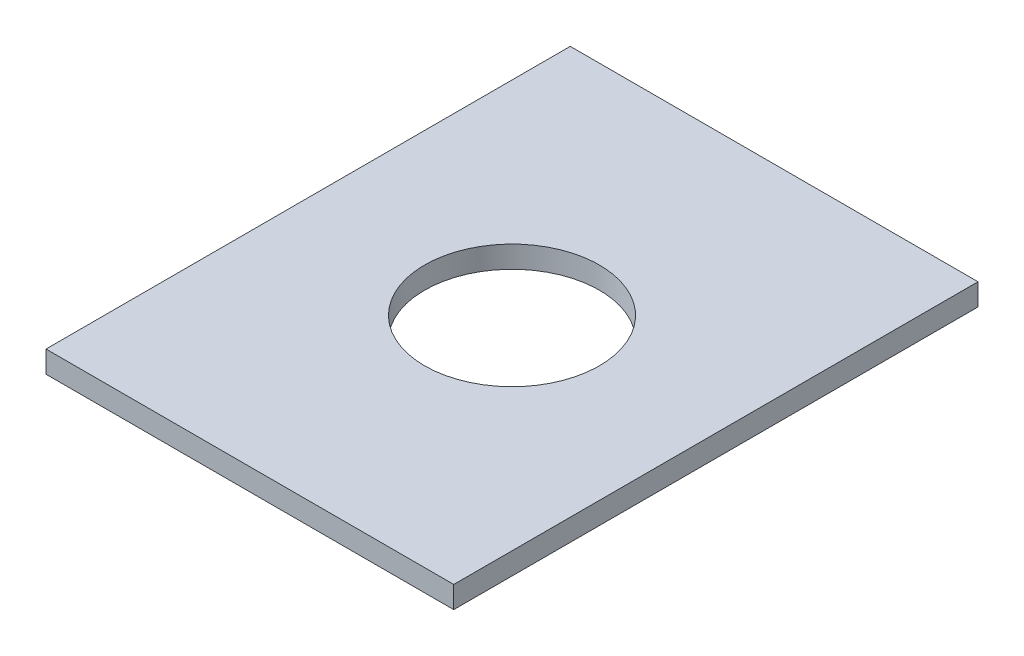
SolidWorks part; units mm, degrees
material "Acrylic (Medium-high impact)"
ref_plane "Front Plane" through (0, 0, 0) normal (0, 0, 1) x (1, 0, 0)
ref_plane "Top Plane" through (0, 0, 0) normal (0, 1, 0) x (1, 0, 0)
ref_plane "Right Plane" through (0, 0, 0) normal (1, 0, 0) x (0, 0, -1)
sketch "Sketch1" plane through (0, 0, 0) normal (0, 1, 0) x (1, 0, 0)
  line L1 (-88.9, 114.3) -> (88.9, 114.3)
  line L2 (-88.9, 114.3) -> (-88.9, -114.3)
  line L3 (-88.9, -114.3) -> (88.9, -114.3)
  line L4 (88.9, 114.3) -> (88.9, -114.3)
  line L5 (-88.9, 114.3) -> (88.9, -114.3) construction
  line L6 (-88.9, -114.3) -> (88.9, 114.3) construction
  point P0 (0, 0)
  dimension "D1" = 177.8
  dimension "D2" = 228.6
extrude "Boss-Extrude1" add sketch "Sketch1" along normal blind 9.525 contours L1 L4 L3 L2
sketch "Sketch2" plane through (0, 9.525, 0) normal (0, 1, 0) x (1, 0, 0)
  circle A0 centre (0, 0) radius 38.1
extrude "Cut-Extrude1" cut sketch "Sketch2" against normal through all
